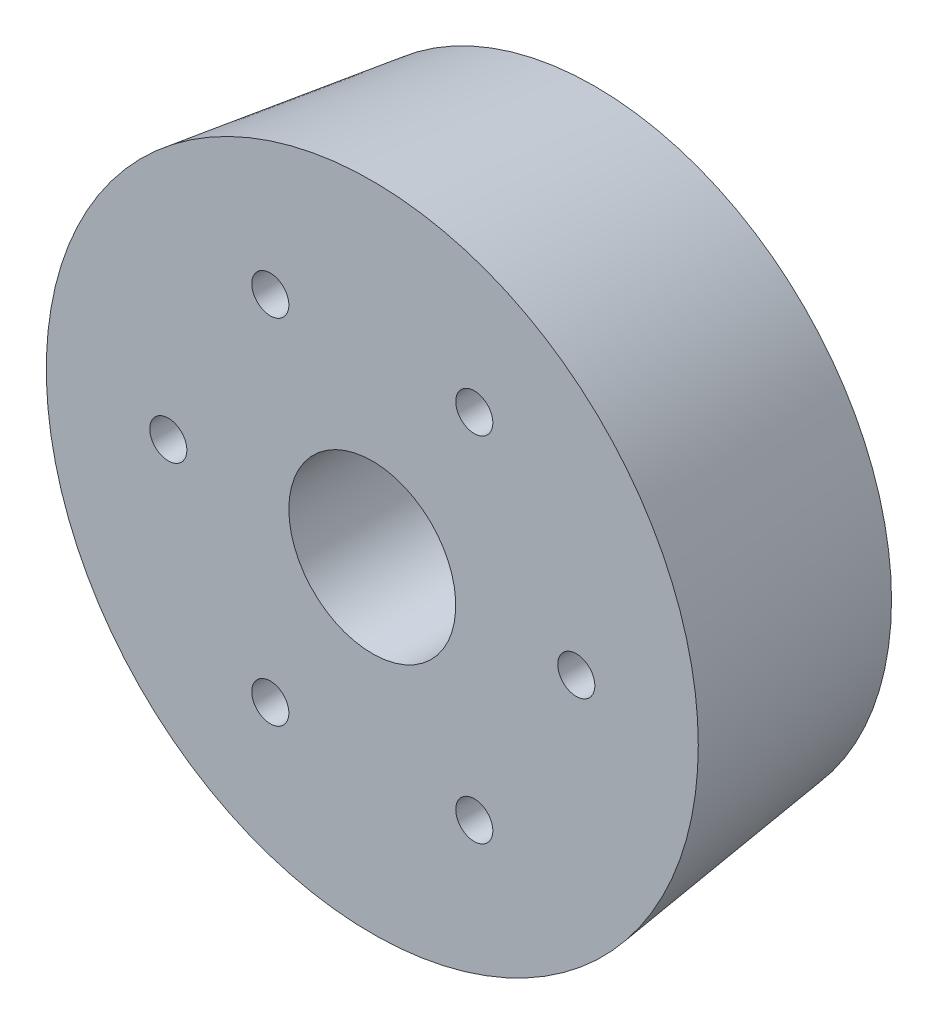
SolidWorks part; units mm, degrees
ref_plane "Front" through (0, 0, 0) normal (0, 0, 1) x (1, 0, 0)
ref_plane "Top" through (0, 0, 0) normal (0, 1, 0) x (1, 0, 0)
ref_plane "Right" through (0, 0, 0) normal (1, 0, 0) x (0, 0, -1)
sketch "Sketch1" plane through (0, 0, 0) normal (0, 0, 1) x (1, 0, 0)
  circle A0 centre (0, 0) radius 50.8
  dimension "D1" = 101.6
extrude "Boss-Extrude1" add sketch "Sketch1" along normal blind 38.1 draft 7.5 draft outward yes
sketch "Sketch2" plane through (0, 0, 0) normal (0, 0, -1) x (-1, 0, 0)
  circle A0 centre (0, 0) radius 14.2875
  dimension "D1" = 28.575
extrude "Cut-Extrude1" cut sketch "Sketch2" against normal blind 38.1
sketch "Sketch3" plane through (0, 0, 0) normal (0, 0, -1) x (-1, 0, 0)
  circle A0 centre (0, 0) radius 34.925 construction
  circle A1 centre (34.925, 0) radius 3.175
  circle A2 centre (17.4625, -30.2459) radius 3.175
  circle A3 centre (0, 0) radius 34.925 construction
  circle A4 centre (-17.4625, -30.2459) radius 3.175
  circle A5 centre (0, 0) radius 34.925 construction
  circle A6 centre (-34.925, 0) radius 3.175
  circle A7 centre (0, 0) radius 34.925 construction
  circle A8 centre (-17.4625, 30.2459) radius 3.175
  circle A9 centre (0, 0) radius 34.925 construction
  circle A10 centre (17.4625, 30.2459) radius 3.175
  circle A11 centre (0, 0) radius 34.925 construction
  point P22 (0, 0)
  dimension "D1" = 69.85
  dimension "D2" = 6.35
  dimension "D3" = 6
extrude "Cut-Extrude2" cut sketch "Sketch3" against normal blind 38.1
